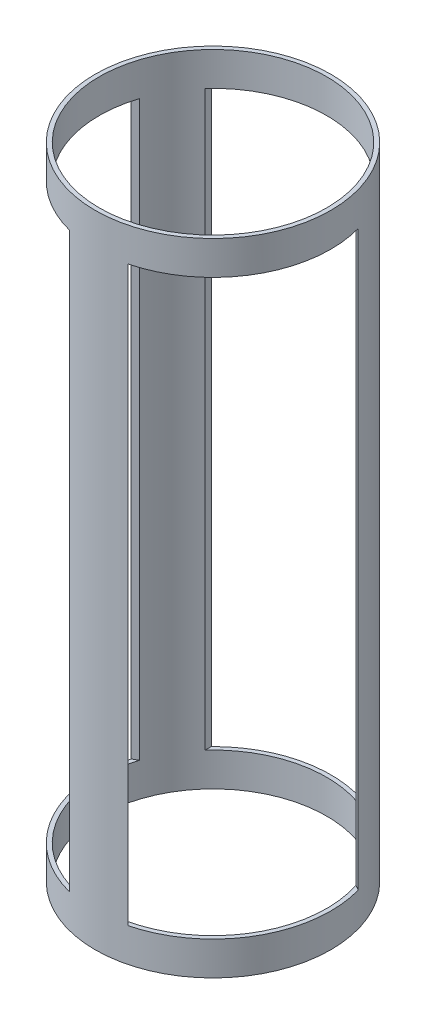
SolidWorks part; units mm, degrees
material "6061-T6 (SS)"
ref_plane "Front Plane" through (0, 0, 0) normal (0, 0, 1) x (1, 0, 0)
ref_plane "Top Plane" through (0, 0, 0) normal (0, 1, 0) x (1, 0, 0)
ref_plane "Right Plane" through (0, 0, 0) normal (1, 0, 0) x (0, 0, -1)
sketch "Sketch1" plane through (0, 0, 0) normal (0, 1, 0) x (1, 0, 0)
  circle A0 centre (0, 0) radius 88.9
  circle A1 centre (0, 0) radius 85.725
  dimension "D1" = 177.8
  dimension "D2" = 171.45
extrude "Boss-Extrude1" add sketch "Sketch1" along normal mid plane 482.854
sketch "Sketch2" plane through (0, 0, 0) normal (0, 0, 1) x (1, 0, 0)
  line L0 (85.725, 241.427) -> (-85.725, 241.427) construction
  line L1 (-63.5, -216.027) -> (63.5, -216.027)
  line L2 (-63.5, -216.027) -> (-63.5, 216.027)
  line L3 (-63.5, 216.027) -> (63.5, 216.027)
  line L4 (63.5, -216.027) -> (63.5, 216.027)
  line L5 (-63.5, -216.027) -> (63.5, 216.027) construction
  line L6 (-63.5, 216.027) -> (63.5, -216.027) construction
  line L7 (88.9, -241.427) -> (88.9, 241.427) construction
  point P0 (0, 0)
  dimension "D1" = 25.4
  dimension "D2" = 25.4
extrude "Cut-Extrude1" cut sketch "Sketch2" against normal up to surface (62.217 mm away)
pattern_circular "CirPattern1" count 3 over 360 about axis through (0, 0, 0) along (0, 1, 0) of "Cut-Extrude1"
ref_plane "Plane1" through (88.9, 0, 0) normal (1, 0, 0) x (0, 0, -1)
sketch "Sketch4" plane through (88.9, 0, 0) normal (1, 0, 0) x (0, 0, -1)
  line L0 (0, 97.79) -> (0, -97.79) construction
  line L1 (88.9, 241.427) -> (-88.9, 241.427) construction
  circle A0 centre (0, 235.077) radius 1.4351
  dimension "D1" = 2.8702
  dimension "D2" = 6.35
extrude "Cut-Extrude3" [suppressed] cut sketch "Sketch4" against normal blind 15.24
pattern_circular "CirPattern3" [suppressed] count 12 over 360
mirror "Mirror1" [suppressed] about plane through (0, 0, 0) normal (0, 1, 0)
ref_plane "Plane2" through (0, 0, 88.9) normal (0, 0, 1) x (1, 0, 0)
sketch "Sketch5" [suppressed] plane through (0, 0, 88.9) normal (0, 0, 1) x (1, 0, 0)
  circle A0 centre (0, 78.359) radius 1.4351
  circle A1 centre (0, -78.359) radius 1.4351
  circle A2 centre (0, -235.077) radius 1.4351 construction
  circle A3 centre (0, 235.077) radius 1.4351 construction
  dimension "D1" = 156.718
  dimension "D2" = 156.718
  dimension "D3" = 2.8702
  dimension "D4" = 2.8702
extrude "Cut-Extrude4" [suppressed] cut sketch "Sketch5" against normal blind 22.86
pattern_circular "CirPattern4" [suppressed] count 3 over 360
